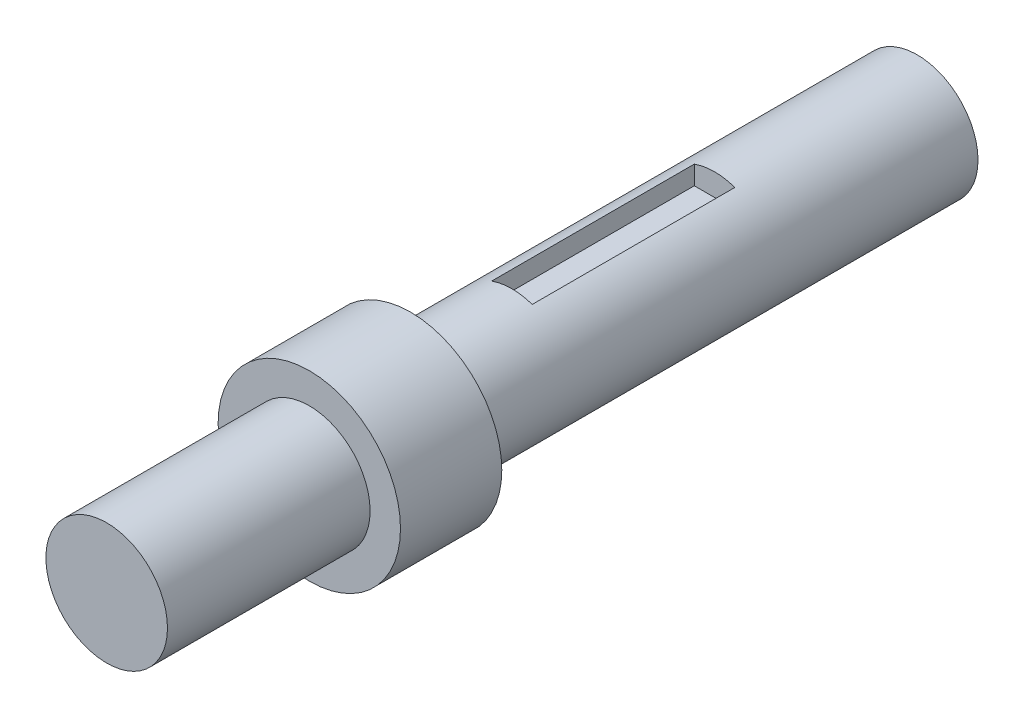
SolidWorks part; units mm, degrees
ref_plane "Front Plane" through (0, 0, 0) normal (0, 0, 1) x (1, 0, 0)
ref_plane "Top Plane" through (0, 0, 0) normal (0, 1, 0) x (1, 0, 0)
ref_plane "Right Plane" through (0, 0, 0) normal (1, 0, 0) x (0, 0, -1)
sketch "Sketch2" plane through (0, 0, 0) normal (0, 0, 1) x (1, 0, 0)
  circle A0 centre (0, 0) radius 6
  dimension "D1" = 12
extrude "Boss-Extrude1" add sketch "Sketch2" along normal blind 50
sketch "Sketch3" plane through (0, 0, 50) normal (0, 0, 1) x (1, 0, 0)
  circle A0 centre (0, 0) radius 9
  dimension "D1" = 18
extrude "Boss-Extrude2" add sketch "Sketch3" along normal blind 10
sketch "Sketch4" plane through (0, 0, 60) normal (0, 0, 1) x (1, 0, 0)
  circle A0 centre (0, 0) radius 6
  dimension "D1" = 12
extrude "Boss-Extrude3" add sketch "Sketch4" along normal blind 20
ref_plane "Plane1" through (0, 6, 0) normal (0, 1, 0) x (1, 0, 0)
sketch "Sketch6" plane through (0, 6, 0) normal (0, 1, 0) x (1, 0, 0)
  line L0 (9, -50) -> (-9, -50) construction
  line L1 (-2, -40) -> (2, -40)
  line L2 (-2, -40) -> (-2, -20)
  line L3 (-2, -20) -> (2, -20)
  line L4 (2, -40) -> (2, -20)
  point P6 (0, -40)
  point P7 (0, -50)
  dimension "D1" = 20
  dimension "D2" = 10
  dimension "D3" = 4
extrude "Cut-Extrude1" cut sketch "Sketch6" against normal blind 2.2
